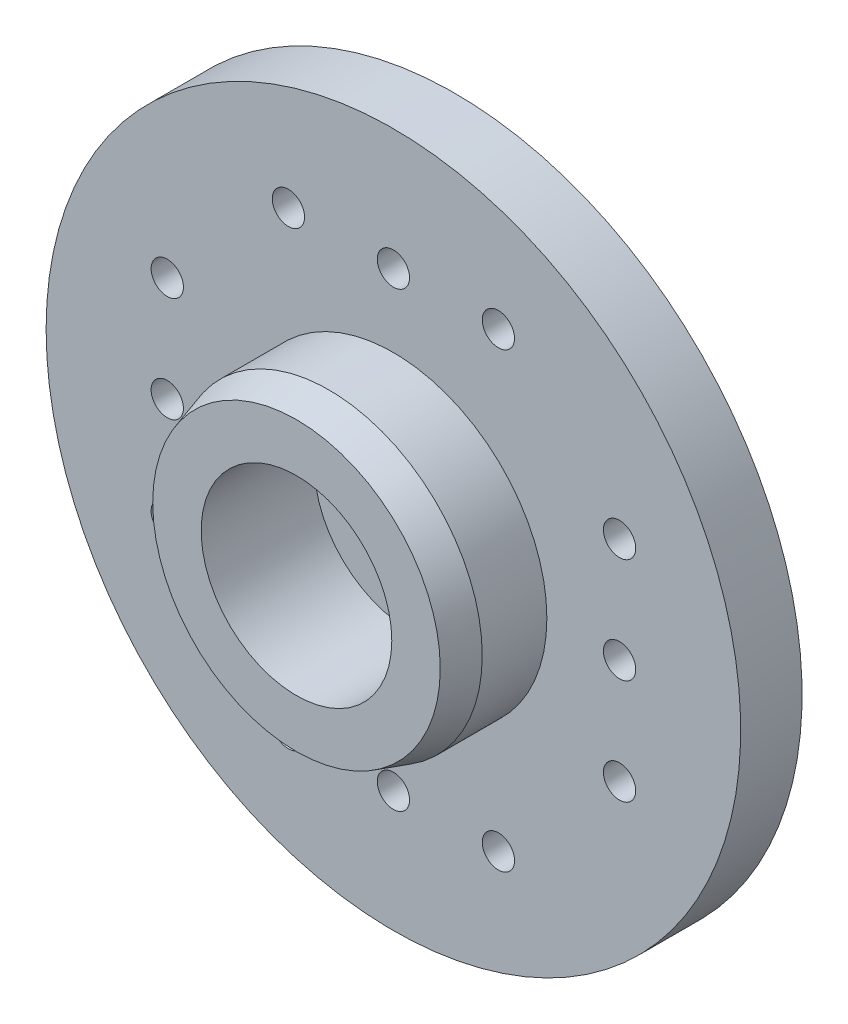
SolidWorks part; units mm, degrees
ref_plane "Front Plane" through (0, 0, 0) normal (0, 0, 1) x (1, 0, 0)
ref_plane "Top Plane" through (0, 0, 0) normal (0, 1, 0) x (1, 0, 0)
ref_plane "Right Plane" through (0, 0, 0) normal (1, 0, 0) x (0, 0, -1)
sketch "Sketch1" plane through (0, 0, 0) normal (0, 0, 1) x (1, 0, 0)
  line L0 (-3.25, 7) -> (3.25, 7) construction
  circle A0 centre (0, 0) radius 10.75
  circle A1 centre (-3.25, 7) radius 0.5
  circle A2 centre (0, 7) radius 0.5
  circle A3 centre (3.25, 7) radius 0.5
  circle A4 centre (7, 3.25) radius 0.5
  circle A5 centre (7, 0) radius 0.5
  circle A6 centre (7, -3.25) radius 0.5
  circle A7 centre (3.25, -7) radius 0.5
  circle A8 centre (0, -7) radius 0.5
  circle A9 centre (-3.25, -7) radius 0.5
  circle A10 centre (-7, -3.25) radius 0.5
  circle A11 centre (-7, 0) radius 0.5
  circle A12 centre (-7, 3.25) radius 0.5
  point P9 (0, 7)
  point P31 (0, 0)
  dimension "D1" = 21.5
  dimension "D4" = 1
  dimension "D2" = 6.5
  dimension "D3" = 7
  dimension "D5" = 4
extrude "Boss-Extrude1" add sketch "Sketch1" along normal blind 1.9
sketch "Sketch2" plane through (0, 0, 1.9) normal (0, 0, 1) x (1, 0, 0)
  circle A0 centre (0, 0) radius 4.75
  dimension "D1" = 9.5
extrude "Boss-Extrude2" add sketch "Sketch2" along normal blind 3
ref_plane "Plane1" through (0, 0, 3.9) normal (0, 0, 1) x (1, 0, 0)
sketch "Sketch5" plane through (0, 0, 0) normal (0, 1, 0) x (1, 0, 0)
  line L0 (4.75, -3.9) -> (4.45, -4.9)
  line L1 (-11.825, -3.9) -> (11.825, -3.9) construction
  line L2 (4.75, -4.9) -> (4.75, -1.9) construction
  line L3 (-4.75, -4.9) -> (4.75, -4.9) construction
  line L4 (-4.45, -4.9) -> (-4.75, -3.9) construction
  line L5 (-4.45, -4.9) -> (4.45, -4.9) construction
  line L6 (4.45, -4.9) -> (4.75, -4.9)
  line L7 (4.75, -4.9) -> (4.75, -3.9)
  line L8 (0, -6.0984) -> (0, 1.24) construction
  point P10 (0, -4.9)
  dimension "D1" = 8.9
revolve "Cut-Revolve1" cut sketch "Sketch5" angle 360 about L8
sketch "Sketch7" plane through (0, 0, 4.9) normal (0, 0, 1) x (1, 0, 0)
  circle A0 centre (0, 0) radius 2.95
  dimension "D1" = 5.9
extrude "Cut-Extrude1" cut sketch "Sketch7" against normal blind 3.5
sketch "Sketch8" plane through (0, 0, 0) normal (0, 0, -1) x (-1, 0, 0)
  circle A0 centre (0, 0) radius 3.25
  circle A1 centre (0, 0) radius 2.75
  dimension "D1" = 6.5
  dimension "D2" = 0.5
extrude "Boss-Extrude3" add sketch "Sketch8" along normal blind 1
sketch "Sketch9" plane through (0, 0, 0) normal (0, 0, -1) x (-1, 0, 0)
  circle A0 centre (0, 0) radius 3.25
  circle A1 centre (0, 0) radius 4.25
  dimension "D1" = 8.5
extrude "Cut-Extrude2" cut sketch "Sketch9" against normal blind 0.4
sketch "Sketch10" plane through (0, 0, 0) normal (0, 0, -1) x (-1, 0, 0)
  circle A0 centre (0, 0) radius 1.45
  dimension "D1" = 2.9
extrude "Cut-Extrude3" cut sketch "Sketch10" against normal through all
